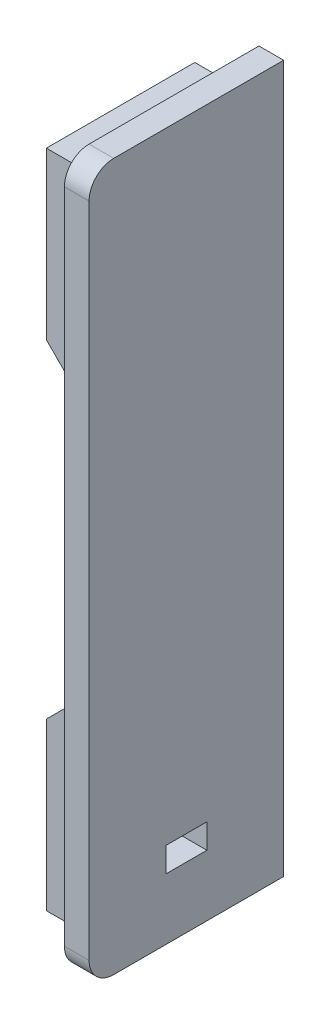
SolidWorks part; units mm, degrees
ref_plane "Front Plane" through (0, 0, 0) normal (0, 0, 1) x (1, 0, 0)
ref_plane "Top Plane" through (0, 0, 0) normal (0, 1, 0) x (1, 0, 0)
ref_plane "Right Plane" through (0, 0, 0) normal (1, 0, 0) x (0, 0, -1)
sketch "Sketch1" plane through (0, 0, 0) normal (1, 0, 0) x (0, 0, -1)
  line L1 (-8.8333, -43) -> (11.8333, -43)
  line L2 (-11.8333, -40) -> (-11.8333, 40)
  line L3 (-8.8333, 43) -> (11.8333, 43)
  line L4 (11.8333, -43) -> (11.8333, 43)
  line L5 (-11.8333, -43) -> (11.8333, 43) construction
  line L6 (-11.8333, 43) -> (11.8333, -43) construction
  arc A2 (-11.8333, -40) -> (-8.8333, -43) centre (-8.8333, -40) ccw
  arc A3 (-8.8333, 43) -> (-11.8333, 40) centre (-8.8333, 40) ccw
  point P0 (0, 0)
  dimension "D1" = 3
extrude "Boss-Extrude1" add sketch "Sketch1" along normal blind 3
sketch "Sketch2" plane through (3, 0, 0) normal (1, 0, 0) x (0, 0, -1)
  line L0 (0, 0) -> (0, -60.8438) construction
  line L1 (-2.5, -35.561) -> (2.5, -35.561)
  line L2 (-2.5, -35.561) -> (-2.5, -32.561)
  line L3 (-2.5, -32.561) -> (2.5, -32.561)
  line L4 (2.5, -35.561) -> (2.5, -32.561)
  line L5 (-2.5, -35.561) -> (2.5, -32.561) construction
  line L6 (-2.5, -32.561) -> (2.5, -35.561) construction
  point P0 (0, -34.061)
extrude "Cut-Extrude1" cut sketch "Sketch2" against normal through all
sketch "Sketch3" plane through (0, 0, 0) normal (-1, 0, 0) x (0, 0, 1)
  line L1 (-9.0271, -40.1707) -> (9.0271, -40.1707)
  line L2 (-9.0271, -40.1707) -> (-9.0271, 40.1707)
  line L3 (-9.0271, 40.1707) -> (9.0271, 40.1707)
  line L4 (9.0271, -40.1707) -> (9.0271, 40.1707)
  line L5 (-9.0271, -40.1707) -> (9.0271, 40.1707) construction
  line L6 (-9.0271, 40.1707) -> (9.0271, -40.1707) construction
  point P0 (0, 0)
extrude "Boss-Extrude2" add sketch "Sketch3" along normal blind 5
sketch "Sketch5" plane through (-5, 0, 0) normal (-1, 0, 0) x (0, 0, 1)
  line L1 (-5.9579, -38.0042) -> (5.9579, -38.0042)
  line L2 (-5.9579, -38.0042) -> (-5.9579, 38.0042)
  line L3 (-5.9579, 38.0042) -> (5.9579, 38.0042)
  line L4 (5.9579, -38.0042) -> (5.9579, 38.0042)
  line L5 (-5.9579, -38.0042) -> (5.9579, 38.0042) construction
  line L6 (-5.9579, 38.0042) -> (5.9579, -38.0042) construction
  point P0 (0, 0)
extrude "Cut-Extrude2" cut sketch "Sketch5" against normal blind 5
sketch "Sketch6" plane through (0, 0, 0) normal (0, 0, 1) x (1, 0, 0)
  line L0 (-5, -40.1707) -> (-5, 40.1707) construction
  line L1 (-5, -19.9742) -> (-1.7149, -16.6891)
  line L3 (-5, 19.9742) -> (-1.7149, 16.6891)
  line L4 (-1.7149, -16.6891) -> (-1.7149, 16.6891)
  line L7 (-5, 19.9742) -> (-5, -19.9742)
  point P0 (-5, 0)
  point P2 (-5, 0)
  dimension "D1" = 45
  dimension "D2" = 45
extrude "Cut-Extrude3" cut sketch "Sketch6" against normal through all and the other way through all
sketch "Sketch7" plane through (0, 0, 0) normal (-1, 0, 0) x (0, 0, 1)
  line L1 (-1, -4.5) -> (1, -4.5)
  line L2 (-1, -4.5) -> (-1, 4.5)
  line L3 (-1, 4.5) -> (1, 4.5)
  line L4 (1, -4.5) -> (1, 4.5)
  line L5 (-1, -4.5) -> (1, 4.5) construction
  line L6 (-1, 4.5) -> (1, -4.5) construction
  point P0 (0, 0)
extrude "Boss-Extrude3" add sketch "Sketch7" along normal blind 5
sketch "Sketch8" plane through (0, 0, 1) normal (0, 0, 1) x (1, 0, 0)
  line L4 (0, -4.5) -> (0, 4.5)
  line L5 (0, 4.5) -> (-5, 4.5)
  line L6 (-5, 4.5) -> (-5, -4.5)
  line L7 (-5, -4.5) -> (0, -4.5)
  line L8 (0, -4.5) -> (0, 4.5)
  line L9 (0, 4.5) -> (-5, 4.5)
  line L10 (-5, 4.5) -> (-5, -4.5)
  line L11 (-5, -4.5) -> (0, -4.5)
  circle A0 centre (-2.5106, 0) radius 2.5315
  arc A1 (-5, -3.7487) -> (0, -3.7345) centre (-2.5106, 0) ccw
  arc A2 (0, 3.7345) -> (-5, 3.7487) centre (-2.5106, 0) ccw
  line M5 (0, -4.5) -> (0, 4.5)
  line M6 (0, 4.5) -> (-5, 4.5)
  line M7 (-5, 4.5) -> (-5, -4.5)
  line M8 (-5, -4.5) -> (0, -4.5)
  dimension "D1" = 0
extrude "Cut-Extrude4" cut sketch "Sketch8" against normal blind 5 contours L8 A0 L10 | A1 L10 M8 | A1 L11 M5 | A2 L8 M6 | A2 L9 M7
sketch "Sketch9" plane through (-5, 0, 0) normal (-1, 0, 0) x (0, 0, 1)
  line L1 (-1.2672, -1) -> (1.2672, -1)
  line L2 (-1.2672, -1) -> (-1.2672, 1)
  line L3 (-1.2672, 1) -> (1.2672, 1)
  line L4 (1.2672, -1) -> (1.2672, 1)
  line L5 (-1.2672, -1) -> (1.2672, 1) construction
  line L6 (-1.2672, 1) -> (1.2672, -1) construction
  point P0 (0, 0)
extrude "Cut-Extrude5" cut sketch "Sketch9" against normal blind 1
sketch "Sketch10" plane through (0, 0, 1) normal (0, 0, 1) x (1, 0, 0)
  line L0 (0, 0) -> (-0.2501, 0) construction
  line L1 (0, 0) -> (-7.6994, 0) construction
  line L2 (0.632, -1.1448) -> (-0.193, -4.4539)
  line L3 (-4.4199, -0.7392) -> (-4.336, -0.6668)
  line L4 (-5.0479, -3.258) -> (-4.4199, -0.7392)
  line L8 (-5.0479, 3.258) -> (-4.4199, 0.7392)
  line L9 (-4.4199, 0.7392) -> (-4.336, 0.6668)
  line L10 (0.632, 1.1448) -> (-0.193, 4.4539)
  arc A0 (-0.193, -4.4539) -> (-5.0479, -3.258) centre (-1.7256, -0.2229) cw
  arc A1 (0.632, -1.1448) -> (-4.336, -0.6668) centre (-1.8112, -0.4824) cw
  arc A4 (0.632, 1.1448) -> (-4.336, 0.6668) centre (-1.8112, 0.4824) ccw
  arc A5 (-0.193, 4.4539) -> (-5.0479, 3.258) centre (-1.7256, 0.2229) ccw
sketch "Sketch12" plane through (0, 0, 1) normal (0, 0, 1) x (1, 0, 0)
  line L3 (-4.8362, -1) -> (-5, -1)
  line L4 (-5, -1) -> (-5, -3.7487)
  line L5 (0, -3.7345) -> (0, -0.3242)
  line L6 (-4.8362, -1) -> (-5, -1)
  line L7 (-5, -1) -> (-5, -3.7487)
  line L8 (0, -3.7345) -> (0, -0.3242)
  line L9 (-5, 3.7487) -> (-5, 1)
  line L10 (-5, 1) -> (-4.8362, 1)
  line L11 (0, 0.3242) -> (0, 3.7345)
  line L12 (-5, 3.7487) -> (-5, 1)
  line L13 (-5, 1) -> (-4.8362, 1)
  line L14 (0, 0.3242) -> (0, 3.7345)
  arc A2 (-4.8362, -1) -> (0, -0.3242) centre (-2.5106, 0) ccw
  arc A3 (-4.8362, -1) -> (0, -0.3242) centre (-2.5106, 0) ccw
  arc A6 (-5, -3.7487) -> (0, -3.7345) centre (-2.5106, 0) ccw
  arc A7 (-5, -3.7487) -> (0, -3.7345) centre (-2.5106, 0) ccw
  arc A10 (0, 0.3242) -> (-4.8362, 1) centre (-2.5106, 0) ccw
  arc A11 (0, 0.3242) -> (-4.8362, 1) centre (-2.5106, 0) ccw
  arc A12 (0, 3.7345) -> (-5, 3.7487) centre (-2.5106, 0) ccw
  arc A13 (0, 3.7345) -> (-5, 3.7487) centre (-2.5106, 0) ccw
  dimension "D1" = 0
  dimension "D2" = 0
extrude "Cut-Extrude6" cut sketch "Sketch12" against normal blind 2
extrude "Boss-Extrude5" add sketch "Sketch10" against normal blind 2
sketch "Sketch13" plane through (0, 0, -1) normal (0, 0, -1) x (-1, 0, 0)
  line L0 (0.193, 4.4539) -> (-0.6174, 4.2448)
  line L1 (0.193, -4.4539) -> (-0.7391, -4.0793)
  line L2 (-0.6174, 4.2448) -> (-0.7391, -4.0793)
  line L3 (0, -3.6798) -> (0, 3.6798)
  line L4 (0.193, 4.4539) -> (0, 3.6798)
  line L5 (0, 3.6798) -> (0, 2.251)
  line L6 (4.336, 0.6668) -> (4.4199, 0.7392)
  line L7 (4.4199, 0.7392) -> (5.0479, 3.258)
  line L9 (0, 3.6798) -> (0, 2.251)
  line L10 (4.336, 0.6668) -> (4.4199, 0.7392)
  line L11 (4.4199, 0.7392) -> (5.0479, 3.258)
  line L12 (0, -2.251) -> (0, -3.6798)
  line L13 (0, -3.6798) -> (0.193, -4.4539)
  line L14 (5.0479, -3.258) -> (4.4199, -0.7392)
  line L15 (4.4199, -0.7392) -> (4.336, -0.6668)
  line L16 (0, -2.251) -> (0, -3.6798)
  line L18 (5.0479, -3.258) -> (4.4199, -0.7392)
  line L19 (4.4199, -0.7392) -> (4.336, -0.6668)
  line L21 (0.193, 4.4539) -> (-0.6174, 4.2448)
  line L22 (-0.7391, -4.0793) -> (0.193, -4.4539)
  line L23 (0, -3.6798) -> (0, 3.6798)
  line L25 (0, -3.6798) -> (0, 3.6798)
  line L26 (-0.6174, 4.2448) -> (0.193, 4.4539)
  line L27 (0, 3.6798) -> (0, -3.6798)
  line L28 (0.193, -4.4539) -> (-0.7391, -4.0793)
  line L29 (0.193, 4.4539) -> (0, 3.6798)
  line L30 (0, -3.6798) -> (0.193, -4.4539)
  arc A2 (4.336, 0.6668) -> (0, 2.251) centre (1.8112, 0.4824) ccw
  arc A3 (5.0479, 3.258) -> (0.193, 4.4539) centre (1.7256, 0.2229) ccw
  arc A6 (0.193, -4.4539) -> (5.0479, -3.258) centre (1.7256, -0.2229) ccw
  arc A7 (0, -2.251) -> (4.336, -0.6668) centre (1.8112, -0.4824) ccw
  line M13 (0, -2.251) -> (0, -3.6798)
  line M14 (0, -3.6798) -> (0.193, -4.4539)
  dimension "D1" = 0
  dimension "D2" = 0
extrude "Boss-Extrude6" add sketch "Sketch13" against normal blind 2 contours L29 L0 L2 L1 L3 M14 M13
sketch "Sketch15" plane through (0, 0, -1) normal (0, 0, -1) x (-1, 0, 0)
  line L0 (0, 0) -> (6.6968, 0) construction
  line L1 (5.0479, 3.258) -> (4.0385, 1.6855)
  line L2 (4.0385, 1.6855) -> (4.7339, 1.6855)
  line L3 (4.0385, 1.6855) -> (4.0385, -1.6855)
  line L4 (0.193, 4.4539) -> (0, 4.4041)
  line L5 (0, 4.4041) -> (0, 2.251)
  line L6 (4.336, 0.6668) -> (4.4199, 0.7392)
  line L7 (4.4199, 0.7392) -> (5.0479, 3.258)
  line L8 (0.193, 4.4539) -> (0, 4.4041)
  line L9 (0, 4.4041) -> (0, 2.251)
  line L10 (4.336, 0.6668) -> (4.4199, 0.7392)
  line L11 (4.4199, 0.7392) -> (5.0479, 3.258)
  line L12 (0, -2.251) -> (0, -4.3763)
  line L13 (0, -4.3763) -> (0.193, -4.4539)
  line L14 (5.0479, -3.258) -> (4.4199, -0.7392)
  line L15 (4.4199, -0.7392) -> (4.336, -0.6668)
  line L16 (0, -2.251) -> (0, -4.3763)
  line L17 (0, -4.3763) -> (0.193, -4.4539)
  line L18 (5.0479, -3.258) -> (4.4199, -0.7392)
  line L19 (4.4199, -0.7392) -> (4.336, -0.6668)
  line L20 (4.0385, -1.6855) -> (4.7339, -1.6855)
  line L21 (4.7339, 1.6855) -> (4.7339, -1.6855)
  line L22 (4.0385, 1.6855) -> (4.7339, -1.6855) construction
  line L23 (4.0385, -1.6855) -> (4.7339, 1.6855) construction
  line L24 (5.0479, -3.258) -> (4.0385, -1.6855)
  arc A1 (0, -2.251) -> (4.336, -0.6668) centre (1.8112, -0.4824) ccw construction
  arc A2 (5.0479, 3.258) -> (0.193, 4.4539) centre (1.7256, 0.2229) ccw
  arc A3 (4.336, 0.6668) -> (0, 2.251) centre (1.8112, 0.4824) ccw
  arc A4 (5.0479, 3.258) -> (0.193, 4.4539) centre (1.7256, 0.2229) ccw
  arc A5 (4.336, 0.6668) -> (0, 2.251) centre (1.8112, 0.4824) ccw
  arc A6 (0.193, -4.4539) -> (5.0479, -3.258) centre (1.7256, -0.2229) ccw
  arc A7 (0, -2.251) -> (4.336, -0.6668) centre (1.8112, -0.4824) ccw
  arc A8 (0.193, -4.4539) -> (5.0479, -3.258) centre (1.7256, -0.2229) ccw
  arc A9 (0, -2.251) -> (4.336, -0.6668) centre (1.8112, -0.4824) ccw
  arc A10 (4.336, 0.6668) -> (0, 2.251) centre (1.8112, 0.4824) ccw construction
  point P8 (4.3862, 0)
  arc M21 (0, 2.251) -> (4.336, 0.6668) centre (1.8112, 0.4824) cw
  line M22 (4.336, 0.6668) -> (4.4199, 0.7392)
  line M23 (4.4199, 0.7392) -> (5.0479, 3.258)
  dimension "D1" = 0
  dimension "D2" = 0
extrude "Cut-Extrude7" cut sketch "Sketch15" against normal blind 2 contours L1 L2 M23 | L2 M21 M22 M23 | A9 L20 L18 L19 | L24 L18 L20
